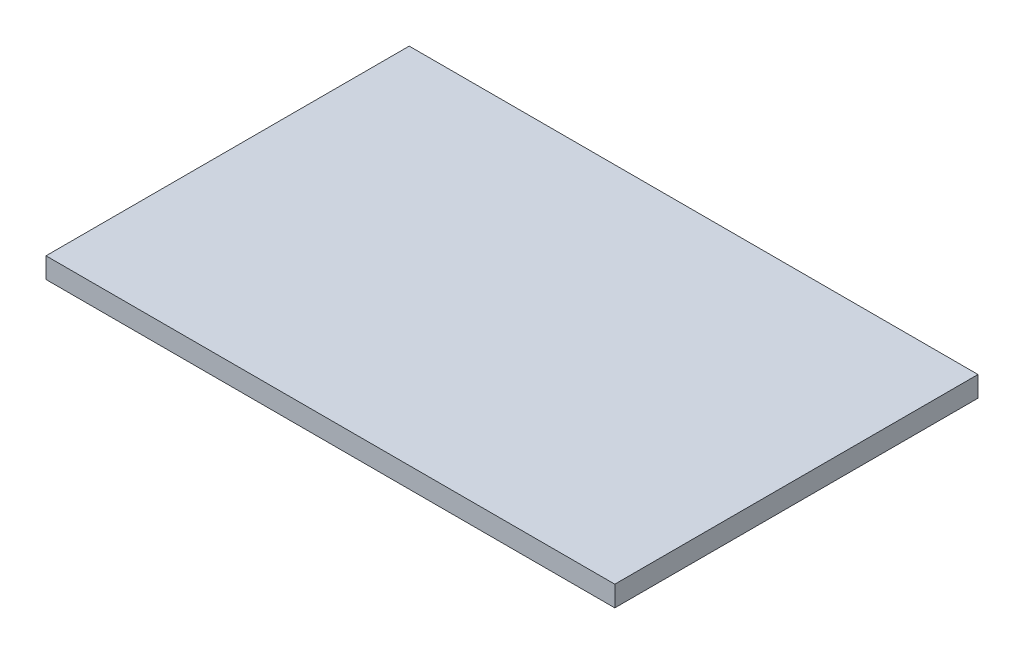
SolidWorks part; units mm, degrees
ref_plane "Front Plane" through (0, 0, 0) normal (0, 0, 1) x (1, 0, 0)
ref_plane "Top Plane" through (0, 0, 0) normal (0, 1, 0) x (1, 0, 0)
ref_plane "Right Plane" through (0, 0, 0) normal (1, 0, 0) x (0, 0, -1)
sketch "Sketch1" plane through (0, 0, 0) normal (0, 1, 0) x (1, 0, 0)
  line L1 (41.5, 26.5) -> (-41.5, 26.5)
  line L2 (41.5, 26.5) -> (41.5, -26.5)
  line L3 (41.5, -26.5) -> (-41.5, -26.5)
  line L4 (-41.5, 26.5) -> (-41.5, -26.5)
  line L5 (41.5, 26.5) -> (-41.5, -26.5) construction
  line L6 (41.5, -26.5) -> (-41.5, 26.5) construction
  point P0 (0, 0)
  dimension "D1" = 83
  dimension "D2" = 53
extrude "Boss-Extrude1" add sketch "Sketch1" along normal blind 3
